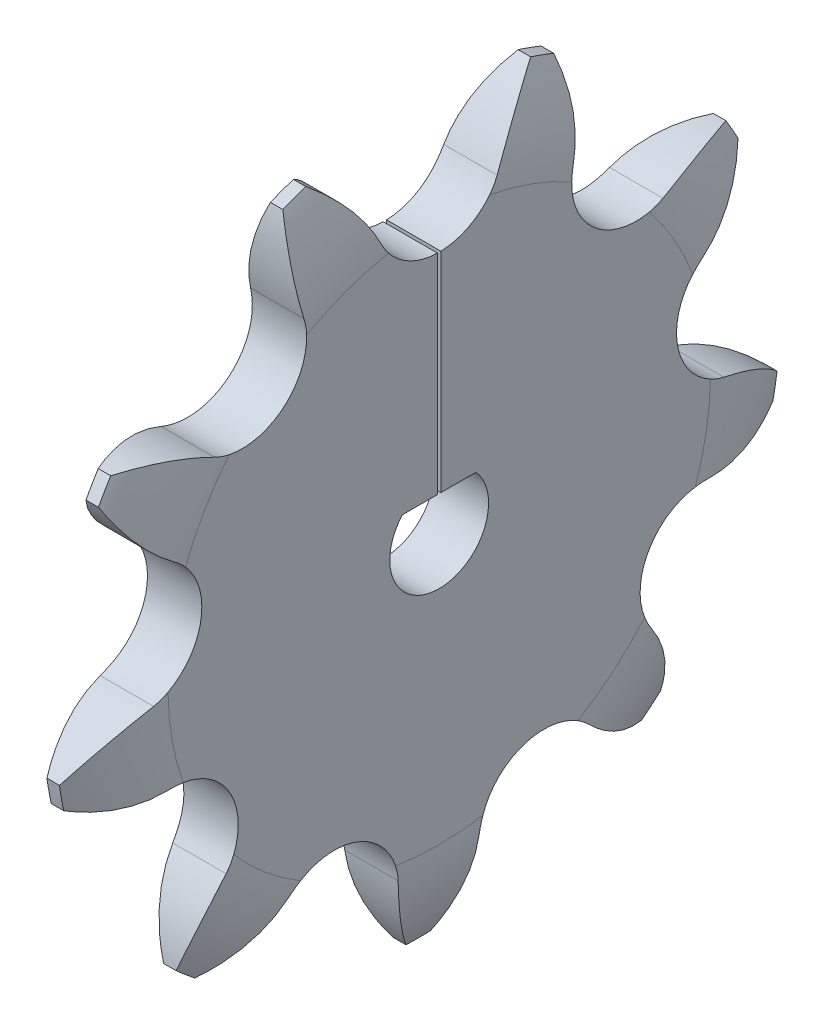
SolidWorks part; units mm, degrees
ref_plane "Plano frontal" through (0, 0, 0) normal (0, 0, 1) x (1, 0, 0)
ref_plane "Plano superior" through (0, 0, 0) normal (0, 1, 0) x (1, 0, 0)
ref_plane "Plano direito" through (0, 0, 0) normal (1, 0, 0) x (0, 0, -1)
sketch "Esboço2" plane through (0, 0, 0) normal (0, 0, 1) x (1, 0, 0)
  line L0 (0, 0) -> (60, 0) construction
  line L1 (0, 0) -> (0, 16.4642)
  line L2 (0, 0) -> (3.3, 0)
  line L3 (3.3, 0) -> (3.3, 16.4642)
  line L4 (2.03, 22) -> (1.27, 22)
  arc A0 (0, 16.4642) -> (1.27, 22) centre (12.7, 16.4642) cw
  arc A1 (3.3, 16.4642) -> (2.03, 22) centre (-9.4, 16.4642) ccw
  dimension "D1" = 12.7
  dimension "G1" = 1.27
  dimension "G2" = 1.27
  dimension "Diameter" = 44
  dimension "Thickness" = 3.3
revolve "Revolução1" add sketch "Esboço2" angle 360 about L0
sketch "Esboço5" plane through (0, 0, 0) normal (1, 0, 0) x (0, 0, -1)
  line L0 (0, 18.6049) -> (3.5471, 16.9509) construction
  line L1 (0, 0) -> (0, 133.4326) construction
  line L2 (0, 18.6049) -> (-10, 18.6049) construction
  line L3 (0, 18.6049) -> (-3.5471, 16.9509) construction
  arc A0 (3.5471, 16.9509) -> (8.0549, 21.6807) centre (12.8186, 12.6275) cw
  arc A1 (3.5471, 16.9509) -> (-3.5471, 16.9509) centre (0, 18.6049) cw
  arc A2 (-3.5471, 16.9509) -> (-8.0549, 21.6807) centre (-12.8186, 12.6275) ccw
  arc A3 (8.0549, 21.6807) -> (-8.0549, 21.6807) centre (0, 0) ccw
  dimension "D1" = 18.6049
  dimension "D2" = 3.9137
  dimension "D4" = 10.23
  dimension "D5" = 23.1287
  dimension "D3" = 130
extrude "Corte-extrusão1" cut sketch "Esboço5" along normal through all
pattern_circular "PadrãoCircular2" count 9 over 360 about axis through (0, 0, 0) along (1, 0, 0) of "Corte-extrusão1"
sketch "Esboço6" plane through (3.3, 0, 0) normal (1, 0, 0) x (0, 0, -1)
  line L0 (-2.2361, 2) -> (2.2361, 2)
  arc A0 (-2.2361, 2) -> (2.2361, 2) centre (0, 0) ccw
  dimension "D1" = 6
  dimension "D2" = 2
extrude "Corte-extrusão2" cut sketch "Esboço6" against normal through all
sketch "Esboço7" plane through (3.3, 0, 0) normal (1, 0, 0) x (0, 0, -1)
  line L0 (2.2361, 2) -> (-2.2361, 2) construction
  line L1 (-0.1, 2) -> (0.1, 2)
  line L2 (-0.1, 2) -> (-0.1, 32)
  line L3 (-0.1, 32) -> (0.1, 32)
  line L4 (0.1, 2) -> (0.1, 32)
  line L5 (0, 0) -> (0, 18.8617) construction
  dimension "D1" = 0.2
  dimension "D2" = 30
extrude "Corte-extrusão3" cut sketch "Esboço7" against normal blind 10
